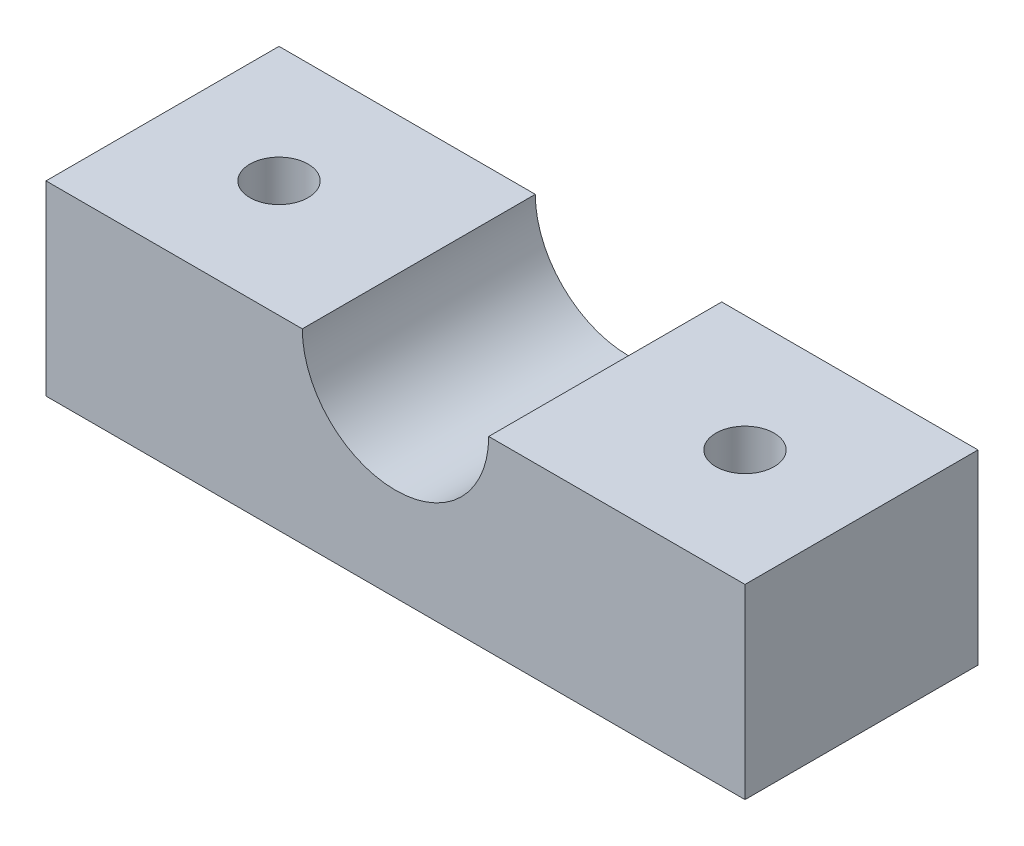
SolidWorks part; units mm, degrees
ref_plane "Ebene vorne" through (0, 0, 0) normal (0, 0, 1) x (1, 0, 0)
ref_plane "Ebene oben" through (0, 0, 0) normal (0, 1, 0) x (1, 0, 0)
ref_plane "Ebene rechts" through (0, 0, 0) normal (1, 0, 0) x (0, 0, -1)
sketch "Skizze1" plane through (0, 0, 0) normal (0, 0, 1) x (1, 0, 0)
  line L0 (19, 8) -> (30, 8)
  line L1 (0, 0) -> (30, 0)
  line L2 (0, 0) -> (0, 8)
  line L3 (0, 8) -> (11, 8)
  line L4 (30, 0) -> (30, 8)
  arc A0 (11, 8) -> (19, 8) centre (15, 8) ccw
  dimension "D4" = 8
  dimension "D1" = 30
  dimension "D2" = 8
  dimension "D3" = 15
extrude "Aufsatz-Linear austragen1" add sketch "Skizze1" along normal blind 10
hole_wizard "M3 Gewindebohrung1" positions "Skizze2" profile "Skizze3" tap size "M3" standard "DIN" end condition up to next
sketch "Skizze2" plane through (0, 0, 0) normal (0, -1, 0) x (-1, 0, 0)
  line L0 (0, -10) -> (-30, -10) construction
  line L1 (-30, -10) -> (-30, 0) construction
  line L2 (0, -10) -> (0, 0) construction
  point P0 (-5, -5)
  point P2 (-25, -5)
  dimension "D1" = 5
  dimension "D2" = 5
  dimension "D3" = 5
  dimension "D4" = 5
sketch "Skizze3" plane through (5, 0, 5) normal (1, 0, 0) x (0, 0, -1)
  line L0 (0, 0) -> (0, 8)
  line L1 (0, 8) -> (1.25, 8)
  line L2 (1.25, 8) -> (1.25, 0)
  line L5 (1.25, 0) -> (0, 0)
  line L11 (0, -6.35) -> (0, 107.95) construction
  dimension "Bohrerdurchmesser" = 2.5
  dimension "Bohrungstiefe" = 8
cosmetic thread "Bohrungsgewinde1" parameters "D2"=3
cosmetic thread "Bohrungsgewinde2" parameters "D2"=3
